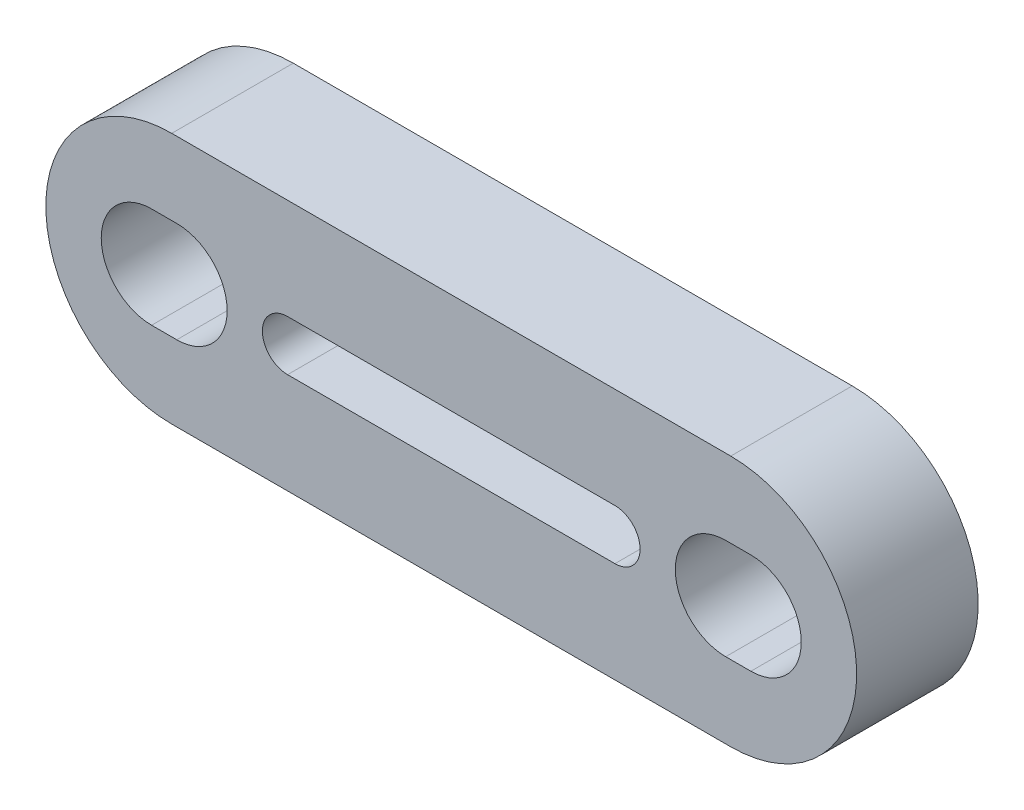
SolidWorks part; units mm, degrees
material "1100-H12 Rod (SS)"
ref_plane "Front Plane" through (0, 0, 0) normal (0, 0, 1) x (1, 0, 0)
ref_plane "Top Plane" through (0, 0, 0) normal (0, 1, 0) x (1, 0, 0)
ref_plane "Right Plane" through (0, 0, 0) normal (1, 0, 0) x (0, 0, -1)
sketch "Sketch1" plane through (0, 0, 0) normal (0, 0, 1) x (1, 0, 0)
  line L0 (0, 0) -> (1, 0) construction
  line L1 (0, 2) -> (1, 2)
  line L2 (0, -2) -> (1, -2)
  line L3 (22.8, 0) -> (23.8, 0) construction
  line L4 (22.8, 2) -> (23.8, 2)
  line L5 (22.8, -2) -> (23.8, -2)
  line L12 (18.4, 0) -> (5.4, 0) construction
  line L15 (18.4, -1) -> (5.4, -1)
  line L18 (18.4, 1) -> (5.4, 1)
  line L21 (11.9, 5) -> (11.9, -5) construction
  line L51 (0, 0) -> (22.8, 0) construction
  line L53 (0.8, 5) -> (23, 5)
  line L55 (0.8, -5) -> (23, -5)
  arc A0 (0, 2) -> (0, -2) centre (0, 0) ccw
  arc A1 (1, -2) -> (1, 2) centre (1, 0) ccw
  arc A2 (22.8, 2) -> (22.8, -2) centre (22.8, 0) ccw
  arc A3 (23.8, -2) -> (23.8, 2) centre (23.8, 0) ccw
  arc A34 (0.8, -5) -> (0.8, 5) centre (0.8, 0) cw
  arc A36 (0, -2) -> (0, 2) centre (0, 0) ccw
  arc A37 (18.4, -1) -> (18.4, 1) centre (18.4, 0) ccw
  arc A38 (5.4, 1) -> (5.4, -1) centre (5.4, 0) ccw
  arc A39 (23, -5) -> (23, 5) centre (23, 0) ccw
  point P3 (0.5, 0)
  point P11 (23.3, 0)
  point P25 (11.9, 0)
  dimension "D1" = 2
  dimension "D5" = 1
  dimension "D10" = 2.2
  dimension "D2" = 1
  dimension "D4" = 22.8
  dimension "D6" = 13
  dimension "D7" = 10
  dimension "D8" = 5.4
  dimension "D3" = 2
extrude "Boss-Extrude1" add sketch "Sketch1" along normal blind 3.175 and the other way blind 1.651
sketch "Sketch2" plane through (0, 0, 0) normal (0, 0, 1) x (1, 0, 0)
  line L0 (5.8, 5) -> (5.8, -5)
  line L1 (0.8, 5) -> (23, 5) construction
  line L2 (0.8, -5) -> (23, -5) construction
  line L3 (18, 5) -> (18, -5)
  line L4 (0.8, 5) -> (5.8, 5)
  line L5 (5.8, 5) -> (18, 5)
  line L6 (18, 5) -> (23, 5)
  line L7 (18, -5) -> (23, -5)
  line L8 (5.8, -5) -> (18, -5)
  line L9 (0.8, -5) -> (5.8, -5)
  arc A0 (0.8, 5) -> (0.8, -5) centre (0.8, 0) ccw construction
  arc A1 (23, -5) -> (23, 5) centre (23, 0) ccw construction
  arc A2 (0.8, 5) -> (0.8, -5) centre (0.8, 0) ccw
  arc A3 (23, -5) -> (23, 5) centre (23, 0) ccw
  circle A4 centre (0.8, 0) radius 5
  circle A5 centre (23, 0) radius 5
